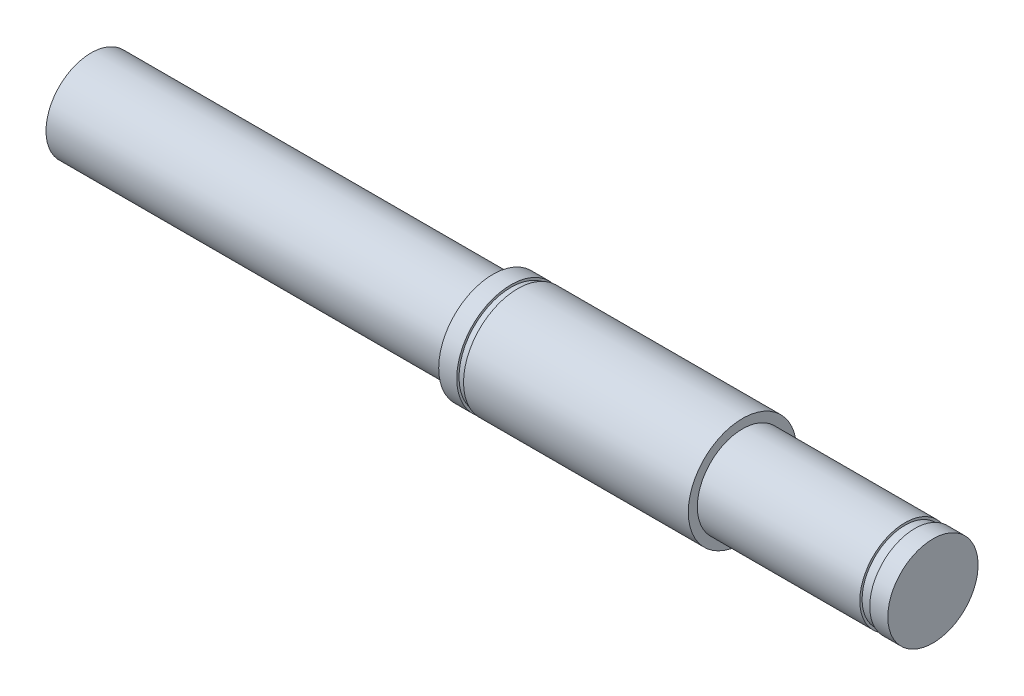
SolidWorks part; units mm, degrees
ref_plane "Front Plane" through (0, 0, 0) normal (0, 0, 1) x (1, 0, 0)
ref_plane "Top Plane" through (0, 0, 0) normal (0, 1, 0) x (1, 0, 0)
ref_plane "Right Plane" through (0, 0, 0) normal (1, 0, 0) x (0, 0, -1)
sketch "Sketch2" plane through (0, 0, 0) normal (0, 0, 1) x (1, 0, 0)
  line L0 (-46.5, 0) -> (46.75, 0) construction
  line L1 (-46.5, 0) -> (-46.5, 5)
  line L2 (-46.5, 5) -> (-2, 5)
  line L3 (-2, 5) -> (-2, 6)
  line L4 (-2, 6) -> (0, 6)
  line L5 (0, 6) -> (0, 5.75)
  line L6 (0, 5.75) -> (0.75, 5.75)
  line L7 (0.75, 5.75) -> (0.75, 6)
  line L8 (0.75, 6) -> (25.65, 6)
  line L9 (25.65, 6) -> (25.65, 5)
  line L10 (25.65, 5) -> (43.65, 5)
  line L11 (43.65, 5) -> (43.65, 4.75)
  line L12 (43.65, 4.75) -> (44.75, 4.75)
  line L13 (44.75, 5) -> (46.75, 5)
  line L14 (46.75, 5) -> (46.75, 0)
  line L15 (44.75, 4.75) -> (44.75, 5)
  line L16 (-46.5, 0) -> (46.75, 0)
  point P17 (0, 0)
  dimension "D1" = 44.5
  dimension "D2" = 5
  dimension "D3" = 6
  dimension "D4" = 2
  dimension "D5" = 0.25
  dimension "D6" = 18
  dimension "D7" = 1.1
  dimension "D8" = 2
  dimension "D9" = 5
  dimension "D10" = 0.25
  dimension "D11" = 24.9
  dimension "D12" = 0.75
revolve "Revolve1" add sketch "Sketch2" angle 360 about L0
